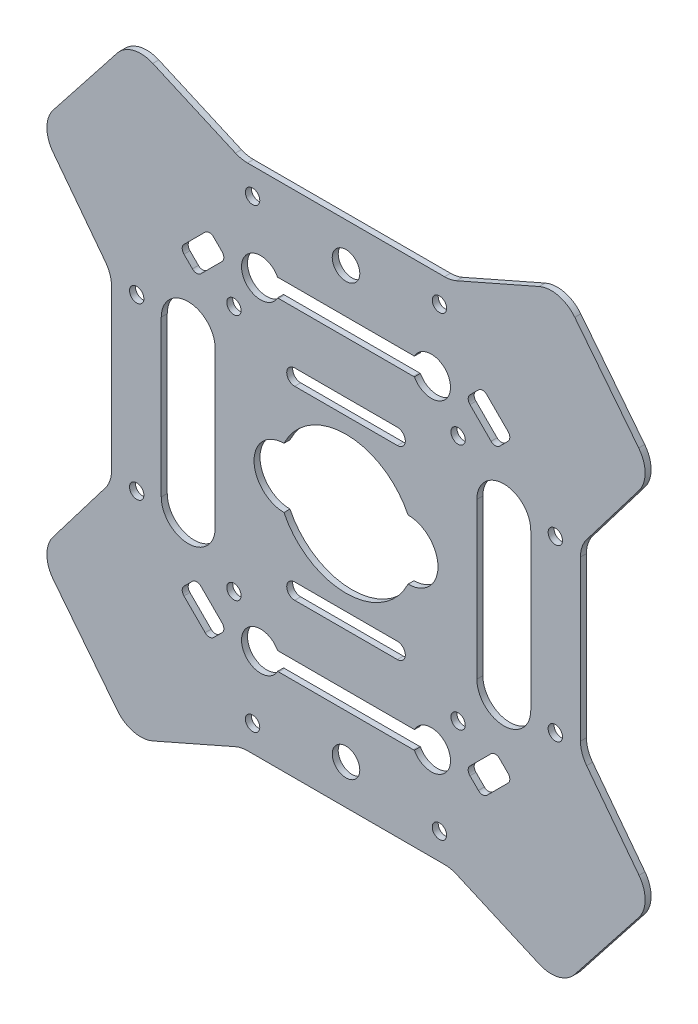
SolidWorks part; units mm, degrees
ref_plane "Front Plane" through (0, 0, 0) normal (0, 0, 1) x (1, 0, 0)
ref_plane "Top Plane" through (0, 0, 0) normal (0, 1, 0) x (1, 0, 0)
ref_plane "Right Plane" through (0, 0, 0) normal (1, 0, 0) x (0, 0, -1)
sketch "Sketch1" plane through (0, 0, 0) normal (0, 0, 1) x (1, 0, 0)
  line L0 (0, 45.5131) -> (0, -9.1859) construction
  line L1 (-13.3987, 0) -> (14.6855, 0) construction
  line L2 (-17.5, 42.5) -> (17.5, 42.5)
  line L3 (17.5, 42.5) -> (35.8082, 50.5504)
  line L4 (35.8082, 50.5504) -> (51.273, 30.9075)
  line L5 (51.273, 30.9075) -> (39.1506, 15)
  line L6 (39.1506, 15) -> (39.1506, -15)
  line L7 (43.5406, 40.7289) -> (33.2515, 32.6284) construction
  line L8 (-39.1506, 15) -> (-39.1506, -15)
  line L9 (-51.273, 30.9075) -> (-39.1506, 15)
  line L10 (-35.8082, 50.5504) -> (-51.273, 30.9075)
  line L11 (-17.5, 42.5) -> (-35.8082, 50.5504)
  line L14 (51.273, -30.9075) -> (39.1506, -15)
  line L15 (35.8082, -50.5504) -> (51.273, -30.9075)
  line L16 (17.5, -42.5) -> (35.8082, -50.5504)
  line L17 (-17.5, -42.5) -> (17.5, -42.5)
  line L18 (-17.5, -42.5) -> (-35.8082, -50.5504)
  line L19 (-35.8082, -50.5504) -> (-51.273, -30.9075)
  line L20 (-51.273, -30.9075) -> (-39.1506, -15)
  point P4 (39.1506, 0)
  point P18 (0, 42.5)
  dimension "D1" = 35
  dimension "D2" = 35
  dimension "D3" = 25
  dimension "D4" = 20
  dimension "D5" = 30
  dimension "D6" = 85
extrude "Boss-Extrude1" add sketch "Sketch1" along normal blind 1 contours L2 L3 L4 L5 L6 L14 L15 L16 L17 L18 L19 L20 L8 L9 L10 L11
fillet "Fillet1" radius 5 16 edges at (-39.1506, 15, 0.5) (-51.273, 30.9075, 0.5) (-35.8082, 50.5504, 0.5) (-17.5, 42.5, 0.5) (17.5, 42.5, 0.5) (35.8082, 50.5504, 0.5) (51.273, 30.9075, 0.5) (39.1506, 15, 0.5) (39.1506, -15, 0.5) (51.273, -30.9075, 0.5) (35.8082, -50.5504, 0.5) (17.5, -42.5, 0.5) (-17.5, -42.5, 0.5) (-35.8082, -50.5504, 0.5) (-51.273, -30.9075, 0.5) (-39.1506, -15, 0.5)
sketch "Sketch3" plane through (0, 0, 1) normal (0, 0, 1) x (1, 0, 0)
  line L0 (138.9945, 49.6556) -> (138.9945, -35.3444) construction
  line L1 (92.5149, 7.8621) -> (100.8509, 7.8621)
  line L4 (-26.3506, 13) -> (-26.3506, -13) construction
  line L9 (-21.8506, 13) -> (-21.8506, -13)
  line L10 (-30.8506, 13) -> (-30.8506, -13)
  line L11 (-39.1506, 13.312) -> (-39.1506, -13.312) construction
  line L12 (106.026, 25.2464) -> (106.026, -10.6669)
  line L13 (-27.0577, 25.4213) -> (-23.5222, 28.9569)
  line L14 (-22.108, 28.9569) -> (-20.6938, 27.5426)
  line L15 (-20.6938, 26.1284) -> (-24.2293, 22.5929)
  line L16 (-25.6435, 22.5929) -> (-27.0577, 24.0071)
  line L17 (107.1457, 37.766) -> (136.6408, 7.8621)
  line L18 (136.6408, 7.8621) -> (100.8509, 7.8621)
  line L19 (-25.29, 27.1891) -> (-22.4615, 24.3607) construction
  line L20 (-23.4635, 0) -> (-29.3104, 0) construction
  line L21 (-11.25, -27) -> (11.25, -27) construction
  line L22 (-11.25, -25.5) -> (11.25, -25.5)
  line L23 (-11.25, -28.5) -> (11.25, -28.5)
  line L24 (-16.4493, -42.5) -> (16.4493, -42.5) construction
  line L25 (0, -22.5529) -> (0, -28.5) construction
  line L26 (0, 19.9577) -> (0, 0) construction
  line L27 (0, 0) -> (32.524, 0) construction
  line L28 (-25.29, -27.1891) -> (-22.4615, -24.3607) construction
  line L29 (-25.6435, -22.5929) -> (-27.0577, -24.0071)
  line L30 (-20.6938, -26.1284) -> (-24.2293, -22.5929)
  line L31 (-22.108, -28.9569) -> (-20.6938, -27.5426)
  line L32 (-27.0577, -25.4213) -> (-23.5222, -28.9569)
  line L33 (-10.3562, 0) -> (10.3562, 0) construction
  line L34 (-10.3562, 5) -> (10.3562, 5)
  line L35 (-10.3562, -5) -> (10.3562, -5)
  line L36 (-8.575, -15.475) -> (8.575, -15.475) construction
  line L37 (-8.575, -14.15) -> (8.575, -14.15)
  line L38 (-8.575, -16.8) -> (8.575, -16.8)
  line L39 (0, 22.5529) -> (0, 28.5) construction
  line L40 (-8.575, 15.475) -> (8.575, 15.475) construction
  line L41 (-8.575, 14.15) -> (8.575, 14.15)
  line L42 (-8.575, 16.8) -> (8.575, 16.8)
  line L43 (-11.25, 27) -> (11.25, 27) construction
  line L44 (-11.25, 25.5) -> (11.25, 25.5)
  line L45 (-11.25, 28.5) -> (11.25, 28.5)
  line L46 (25.29, -27.1891) -> (22.4615, -24.3607) construction
  line L47 (23.4635, 0) -> (29.3104, 0) construction
  line L48 (25.29, 27.1891) -> (22.4615, 24.3607) construction
  line L49 (27.0577, -25.4213) -> (23.5222, -28.9569)
  line L50 (22.108, -28.9569) -> (20.6938, -27.5426)
  line L51 (20.6938, -26.1284) -> (24.2293, -22.5929)
  line L52 (25.6435, -22.5929) -> (27.0577, -24.0071)
  line L53 (25.6435, 22.5929) -> (27.0577, 24.0071)
  line L54 (20.6938, 26.1284) -> (24.2293, 22.5929)
  line L55 (22.108, 28.9569) -> (20.6938, 27.5426)
  line L56 (27.0577, 25.4213) -> (23.5222, 28.9569)
  line L57 (26.3506, 13) -> (26.3506, -13) construction
  line L58 (21.8506, 13) -> (21.8506, -13)
  line L59 (30.8506, 13) -> (30.8506, -13)
  arc A2 (-21.8506, 13) -> (-30.8506, 13) centre (-26.3506, 13) ccw
  arc A3 (-30.8506, -13) -> (-21.8506, -13) centre (-26.3506, -13) ccw
  arc A4 (-24.2293, 22.5929) -> (-25.6435, 22.5929) centre (-24.9364, 23.3) cw
  arc A5 (-20.6938, 27.5426) -> (-20.6938, 26.1284) centre (-21.4009, 26.8355) cw
  arc A6 (-23.5222, 28.9569) -> (-22.108, 28.9569) centre (-22.8151, 28.2497) cw
  arc A7 (-27.0577, 25.4213) -> (-27.0577, 24.0071) centre (-26.3506, 24.7142) ccw
  arc A8 (-11.25, -25.5) -> (-11.25, -28.5) centre (-11.25, -27) ccw
  arc A9 (11.25, -28.5) -> (11.25, -25.5) centre (11.25, -27) ccw
  circle A10 centre (-14.25, -27) radius 3.2
  circle A11 centre (14.25, -27) radius 3.2
  arc A12 (-27.0577, -25.4213) -> (-27.0577, -24.0071) centre (-26.3506, -24.7142) cw
  arc A13 (-23.5222, -28.9569) -> (-22.108, -28.9569) centre (-22.8151, -28.2497) ccw
  arc A14 (-20.6938, -27.5426) -> (-20.6938, -26.1284) centre (-21.4009, -26.8355) ccw
  arc A15 (-24.2293, -22.5929) -> (-25.6435, -22.5929) centre (-24.9364, -23.3) ccw
  circle A16 centre (0, 0) radius 11.5
  arc A17 (-10.3562, 5) -> (-10.3562, -5) centre (-10.3562, 0) ccw
  arc A18 (10.3562, -5) -> (10.3562, 5) centre (10.3562, 0) ccw
  arc A19 (-8.575, -14.15) -> (-8.575, -16.8) centre (-8.575, -15.475) ccw
  arc A20 (8.575, -16.8) -> (8.575, -14.15) centre (8.575, -15.475) ccw
  circle A21 centre (14.25, 27) radius 3.2
  circle A22 centre (-14.25, 27) radius 3.2
  arc A23 (-8.575, 14.15) -> (-8.575, 16.8) centre (-8.575, 15.475) cw
  arc A24 (8.575, 16.8) -> (8.575, 14.15) centre (8.575, 15.475) cw
  arc A25 (-11.25, 25.5) -> (-11.25, 28.5) centre (-11.25, 27) cw
  arc A26 (11.25, 28.5) -> (11.25, 25.5) centre (11.25, 27) cw
  arc A27 (24.2293, -22.5929) -> (25.6435, -22.5929) centre (24.9364, -23.3) cw
  arc A28 (20.6938, -27.5426) -> (20.6938, -26.1284) centre (21.4009, -26.8355) cw
  arc A29 (23.5222, -28.9569) -> (22.108, -28.9569) centre (22.8151, -28.2497) cw
  arc A30 (27.0577, -25.4213) -> (27.0577, -24.0071) centre (26.3506, -24.7142) ccw
  arc A31 (27.0577, 25.4213) -> (27.0577, 24.0071) centre (26.3506, 24.7142) cw
  arc A32 (23.5222, 28.9569) -> (22.108, 28.9569) centre (22.8151, 28.2497) ccw
  arc A33 (20.6938, 27.5426) -> (20.6938, 26.1284) centre (21.4009, 26.8355) ccw
  arc A34 (24.2293, 22.5929) -> (25.6435, 22.5929) centre (24.9364, 23.3) ccw
  arc A35 (21.8506, 13) -> (30.8506, 13) centre (26.3506, 13) cw
  arc A36 (30.8506, -13) -> (21.8506, -13) centre (26.3506, -13) cw
  point P6 (-26.3506, 0)
  point P17 (-39.1506, 0)
  point P24 (-24.9364, 21.8858)
  point P29 (-22.8151, 29.664)
  point P32 (-27.7648, 24.7142)
  point P38 (-26.3506, 23.3)
  point P39 (-26.3506, 17.5)
  point P42 (0, -27)
  point P72 (-27.7648, -24.7142)
  point P73 (-22.8151, -29.664)
  point P74 (-24.9364, -21.8858)
  point P78 (0, 0)
  point P85 (0, -15.475)
  point P90 (0, -16.8)
  point P91 (0, -25.5)
  point P100 (0, 15.475)
  point P107 (0, 27)
  point P142 (24.9364, -21.8858)
  point P143 (22.8151, -29.664)
  point P144 (27.7648, -24.7142)
  point P145 (27.7648, 24.7142)
  point P146 (22.8151, 29.664)
  point P147 (24.9364, 21.8858)
  point P150 (26.3506, 0)
  dimension "D2" = 35
  dimension "D6" = 1
  dimension "D11" = 6.4
  dimension "D14" = 23
  dimension "D15" = 19.8
  dimension "D1" = 8.3
  dimension "D3" = 9
  dimension "D4" = 7
  dimension "D5" = 4
  dimension "D7" = 45
  dimension "D8" = 5.8
  dimension "D9" = 22.5
  dimension "D10" = 3
  dimension "D12" = 3
  dimension "D13" = 14
  dimension "D16" = 10
  dimension "D17" = 2.65
  dimension "D18" = 8.7
extrude "Cut-Extrude1" cut sketch "Sketch3" against normal blind 1 contours L10 A3 L9 A2 | L13 A7 L16 A4 L15 A5 L14 A6 | A22 A25 | A25 A22 | A21 A26 | A26 A21 | A26 A21 L45 A25 A22 L44 | L54 A34 L53 A31 L56 A32 L55 A33 | A36 L59 A35 L58 | A24 L42 A23 L41 | L34 A16 | L34 A16 L35 | A16 A18 | L35 A16 | A16 A17 | A9 A11 L22 A8 A10 L23 | L38 A20 L37 A19 | A11 A9 | A11 A9 | A8 A10 | A8 A10 | L30 A15 L29 A12 L32 A13 L31 A14 | L49 A30 L52 A27 L51 A28 L50 A29
sketch "Sketch5" plane through (0, 0, 1) normal (0, 0, 1) x (1, 0, 0)
  line L0 (-11.25, -28.5) -> (11.25, -28.5) construction
  line L1 (13.7175, 0) -> (0, 0) construction
  line L2 (0, 0) -> (0, -11.5) construction
  line L3 (20.6938, -26.1284) -> (24.2293, -22.5929) construction
  line L4 (18.7139, -20.613) -> (22.4615, -24.3607) construction
  line L5 (30.8506, -13) -> (33.1601, -13) construction
  circle A0 centre (0, -35.9) radius 2.3
  circle A2 centre (-15.6, -38.1) radius 1.2
  arc A3 (-10.3562, -5) -> (10.3562, -5) centre (0, 0) ccw construction
  circle A4 centre (15.6, -38.1) radius 1.2
  circle A6 centre (18.7139, -20.613) radius 1.2
  circle A7 centre (34.9506, -14.2) radius 1.2
  circle A8 centre (34.9506, 14.2) radius 1.2
  circle A9 centre (-34.9506, 14.2) radius 1.2
  circle A10 centre (-34.9506, -14.2) radius 1.2
  circle A11 centre (15.6, 38.1) radius 1.2
  circle A12 centre (0, 35.9) radius 2.3
  circle A13 centre (-15.6, 38.1) radius 1.2
  circle A14 centre (-18.7139, -20.613) radius 1.2
  circle A15 centre (18.7139, 20.613) radius 1.2
  circle A16 centre (-18.7139, 20.613) radius 1.2
  dimension "D1" = 4.6
  dimension "D3" = 2.4
  dimension "D8" = 2.4
  dimension "D9" = 2.4
  dimension "D2" = 7.4
  dimension "D4" = 2.2
  dimension "D5" = 15.6
  dimension "D6" = 35.9
  dimension "D7" = 5.3
  dimension "D10" = 4.1
extrude "Cut-Extrude2" cut sketch "Sketch5" against normal blind 1
ref_plane "Plane1" through (0, 0, -1.025) normal (0, 0, -1) x (-1, 0, 0)
sketch "Sketch6" plane through (0, 0, 0) normal (0, 0, -1) x (-1, 0, 0)
  circle A0 centre (0, 0) radius 56.1021 construction
